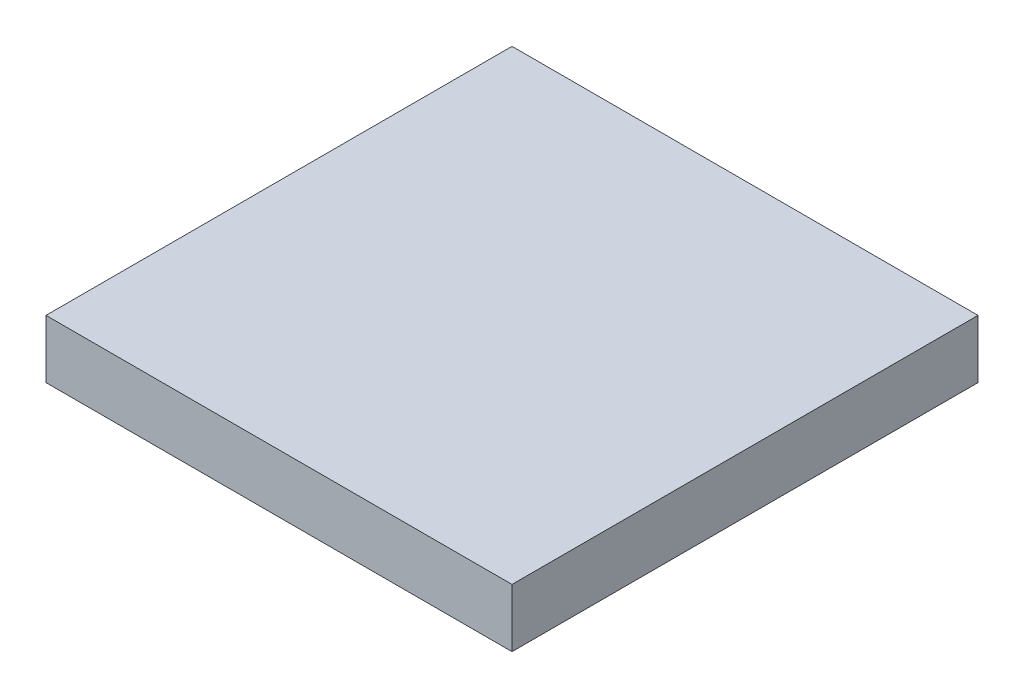
SolidWorks part; units mm, degrees
ref_plane "Front Plane" through (0, 0, 0) normal (0, 0, 1) x (1, 0, 0)
ref_plane "Top Plane" through (0, 0, 0) normal (0, 1, 0) x (1, 0, 0)
ref_plane "Right Plane" through (0, 0, 0) normal (1, 0, 0) x (0, 0, -1)
sketch "Sketch1" plane through (0, 0, 0) normal (0, 0, 1) x (1, 0, 0)
  line L0 (0, -1.5875) -> (0, 1.5875) construction
  line L1 (12.7, 0) -> (-12.7, 0) construction
  point P4 (0, 0)
  point P8 (0, 0)
  dimension "Width" = 25.4
  dimension "Height" = 3.175
sketch "Sketch2" plane through (0, 0, 0) normal (1, 0, 0) x (0, 0, -1)
  line L0 (12.7, 0) -> (-12.7, 0) construction
  point P4 (0, 0)
  dimension "Length" = 25.4
sketch "Sketch3" plane through (0, 0, 0) normal (0, 0, 1) x (1, 0, 0)
  line L1 (-12.7, 1.5875) -> (12.7, 1.5875)
  line L2 (-12.7, 1.5875) -> (-12.7, -1.5875)
  line L3 (-12.7, -1.5875) -> (12.7, -1.5875)
  line L4 (12.7, 1.5875) -> (12.7, -1.5875)
extrude "Boss-Extrude1" add sketch "Sketch3" against normal up to vertex (12.7 mm away) and the other way up to vertex (12.7 mm away) up to point (0, 0, -12.7) other way up to point (0, 0, 12.7)
equation "\"Length@Sketch2\" = \"Width@Sketch1\""
